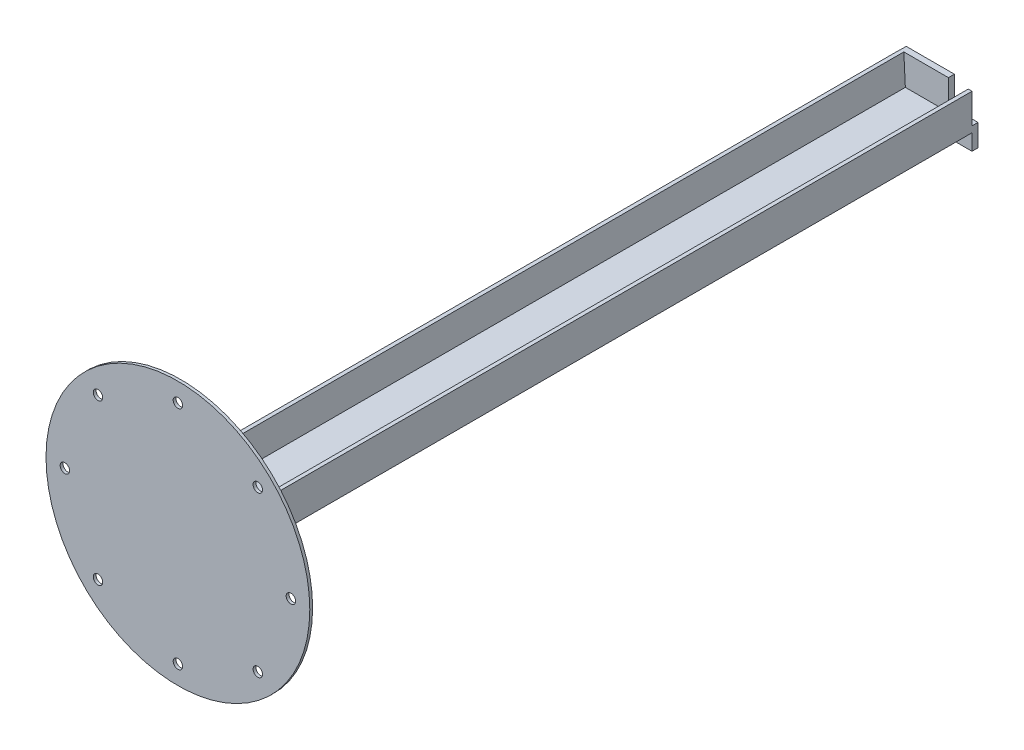
SolidWorks part; units mm, degrees
material "Plain Carbon Steel"
ref_plane "Front Plane" through (0, 0, 0) normal (0, 0, 1) x (1, 0, 0)
ref_plane "Top Plane" through (0, 0, 0) normal (0, 1, 0) x (1, 0, 0)
ref_plane "Right Plane" through (0, 0, 0) normal (1, 0, 0) x (0, 0, -1)
sketch "Sketch1" plane through (0, 0, 0) normal (0, 0, 1) x (1, 0, 0)
  line L0 (0, 0) -> (0, 25.3836) construction
  line L1 (38.1, 0) -> (-38.1, 0)
  line L2 (-38.1, 0) -> (-38.1, 38.1)
  line L3 (-38.1, 38.1) -> (-34.1, 38.1)
  line L4 (-34.1, 38.1) -> (-32.5, 6.35)
  line L5 (-32.5, 6.35) -> (32.5, 6.35)
  line L6 (34.1, 38.1) -> (32.5, 6.35)
  line L7 (38.1, 38.1) -> (34.1, 38.1)
  line L8 (38.1, 0) -> (38.1, 38.1)
  point P9 (0, 6.35)
  dimension "D1" = 76.2
  dimension "D2" = 38.1
  dimension "D3" = 6.35
  dimension "D4" = 4
  dimension "D5" = 65
extrude "Boss-Extrude1" add sketch "Sketch1" along normal blind 800
sketch "Sketch4" plane through (38.1, 0, 0) normal (1, 0, 0) x (0, 0, -1)
  line L0 (-800, 0) -> (0, 0) construction
  line L1 (-800, 38.1) -> (-750, 38.1)
  line L2 (-800, 38.1) -> (-800, 0)
  line L3 (-800, 0) -> (-750, 0)
  line L4 (-750, 38.1) -> (-750, 0)
  dimension "D1" = 50
extrude "Cut-Extrude2" cut sketch "Sketch4" against normal up to vertex (5.6 mm away)
sketch "Sketch5" plane through (0, 6.35, 0) normal (0, 1, 0) x (1, 0, 0)
  line L0 (34.1, -750) -> (34.1, 0) construction
  circle A0 centre (26.1, -765) radius 4
  dimension "D1" = 8
  dimension "D2" = 15
  dimension "D3" = 8
extrude "Boss-Extrude2" add sketch "Sketch5" along normal blind 30
sketch "Sketch6" plane through (32.5, 0, 0) normal (1, 0, 0) x (0, 0, -1)
  line L0 (-800, 38.1) -> (0, 38.1) construction
  line L1 (-800, 0) -> (-780, 0)
  line L2 (-800, 0) -> (-800, 38.1)
  line L3 (-800, 38.1) -> (-780, 38.1)
  line L4 (-780, 0) -> (-780, 38.1)
  dimension "D1" = 20
extrude "Boss-Extrude3" add sketch "Sketch6" along normal blind 5
sketch "Sketch7" plane through (0, 0, 0) normal (0, 0, -1) x (-1, 0, 0)
  line L1 (-38.1, -17) -> (37.9, -17)
  line L2 (-38.1, -17) -> (-38.1, 38.1)
  line L3 (-38.1, 38.1) -> (37.9, 38.1)
  line L4 (37.9, -17) -> (37.9, 38.1)
  line L5 (-38.1, 0) -> (-38.1, 38.1) construction
  line L6 (34.1, 38.1) -> (38.1, 38.1) construction
  line L7 (-32.5, 6.35) -> (32.5, 6.35) construction
  dimension "D1" = 23.35
  dimension "D2" = 76
extrude "Boss-Extrude4" add sketch "Sketch7" along normal blind 6.35
sketch "Sketch8" plane through (0, 0, 800) normal (0, 0, 1) x (1, 0, 0)
  circle A0 centre (0, 15) radius 139.7
  dimension "D1" = 279.4
  dimension "D2" = 15
extrude "Boss-Extrude5" add sketch "Sketch8" along normal blind 3
sketch "Sketch9" plane through (0, 0, -6.35) normal (0, 0, -1) x (-1, 0, 0)
  line L1 (-38.1, 38.1) -> (-13.1, 38.1)
  line L2 (-38.1, 38.1) -> (-38.1, 6.35)
  line L3 (-38.1, 6.35) -> (-13.1, 6.35)
  line L4 (-13.1, 38.1) -> (-13.1, 6.35)
  line L5 (37.9, 38.1) -> (-38.1, 38.1) construction
  line L6 (-32.5, 6.35) -> (32.5, 6.35) construction
  line L7 (-38.1, 38.1) -> (-38.1, -17) construction
  dimension "D1" = 25
extrude "Cut-Extrude3" cut sketch "Sketch9" against normal up to surface (6.35 mm away) up to face at (0, 22.225, 0)
sketch "Sketch10" plane through (0, 0, -6.35) normal (0, 0, -1) x (-1, 0, 0)
  line L0 (-38.1, -17) -> (37.9, -17) construction
  line L1 (-38.1, 6.35) -> (-38.1, -17) construction
  circle A0 centre (-21.1, -6) radius 2.75
  circle A1 centre (16.9, -6) radius 2.75
  dimension "D4" = 5.5
  dimension "D1" = 11
  dimension "D2" = 11
  dimension "D3" = 38
  dimension "D5" = 17
extrude "Cut-Extrude4" cut sketch "Sketch10" against normal up to surface (6.35 mm away) up to face at (0.1, -8.5, 0)
sketch "Sketch11" plane through (0, 0, 803) normal (0, 0, 1) x (1, 0, 0)
  circle A1 centre (0, 134.7) radius 5
  circle A2 centre (0, 15) radius 119.7
  circle A3 centre (0, 15) radius 119.7 construction
  dimension "D2" = 10
  dimension "D1" = 20
extrude "Cut-Extrude5" cut sketch "Sketch11" against normal up to next
pattern_circular "CirPattern1" count 8 over 360 about axis through (0, 15, 0) along (0, 0, 1) of "Cut-Extrude5"
sketch "Sketch12" plane through (-38.1, 0, 0) normal (-1, 0, 0) x (0, 0, 1)
  line L0 (700, 0) -> (800, -100)
  line L1 (800, 0) -> (0, 0) construction
  line L2 (800, 154.7) -> (800, -124.7) construction
  line L3 (800, -100) -> (800, 0)
  line L4 (800, 0) -> (700, 0)
  dimension "D1" = 45
  dimension "D2" = 100
extrude "Boss-Extrude6" add sketch "Sketch12" against normal blind 6
